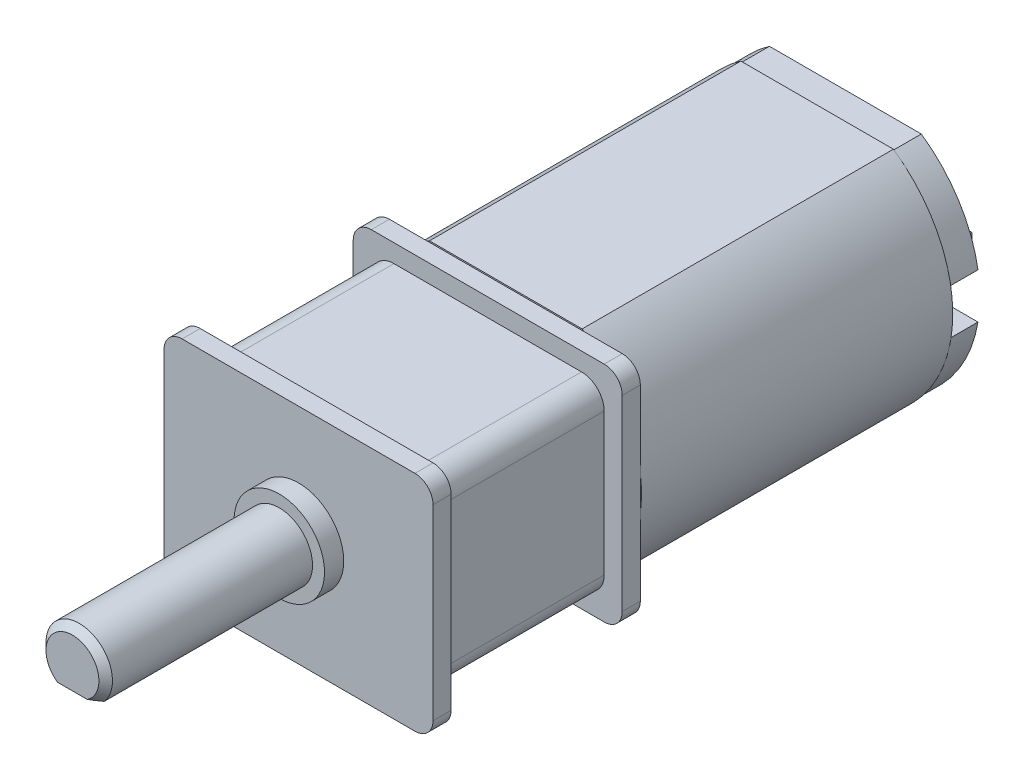
SolidWorks part; units mm, degrees
ref_plane "Front Plane" through (0, 0, 0) normal (0, 0, 1) x (1, 0, 0)
ref_plane "Top Plane" through (0, 0, 0) normal (0, 1, 0) x (1, 0, 0)
ref_plane "Right Plane" through (0, 0, 0) normal (1, 0, 0) x (0, 0, -1)
sketch "Sketch1" plane through (0, 0, 0) normal (0, 0, 1) x (1, 0, 0)
  line L1 (53.6767, -74.8935) -> (60.4267, -74.8935)
  line L3 (60.4267, -84.8935) -> (53.6767, -84.8935)
  arc A0 (53.6767, -74.8935) -> (53.6767, -84.8935) centre (57.1262, -79.8935) ccw
  arc A1 (60.4267, -74.8935) -> (60.4267, -84.8935) centre (56.9773, -79.8935) cw
extrude "Boss-Extrude1" add sketch "Sketch1" against normal blind 16.82
sketch "Sketch2" plane through (0, 0, 0) normal (0, 0, 1) x (1, 0, 0)
  line L3 (63.0017, -84.0335) -> (63.0017, -75.7535)
  line L4 (51.1017, -84.0335) -> (51.1017, -75.7535)
  line L6 (51.9017, -84.8335) -> (62.2017, -84.8335)
  line L7 (51.9017, -74.9535) -> (62.2017, -74.9535)
  arc A0 (51.9017, -74.9535) -> (51.1017, -75.7535) centre (51.9017, -75.7535) ccw
  arc A1 (51.9017, -84.8335) -> (51.1017, -84.0335) centre (51.9017, -84.0335) cw
  arc A2 (62.2017, -84.8335) -> (63.0017, -84.0335) centre (62.2017, -84.0335) ccw
  arc A3 (62.2017, -74.9535) -> (63.0017, -75.7535) centre (62.2017, -75.7535) cw
  dimension "D1" = 0.8
extrude "Boss-Extrude2" add sketch "Sketch2" along normal blind 9.17
sketch "Sketch3" plane through (0, 0, 9.17) normal (0, 0, 1) x (1, 0, 0)
  line L0 (57.0517, -74.9535) -> (57.0517, -84.8335) construction
  line L1 (62.2017, -74.9535) -> (51.9017, -74.9535) construction
  line L2 (51.9017, -84.8335) -> (62.2017, -84.8335) construction
  circle A0 centre (57.0517, -79.8935) radius 2
extrude "Boss-Extrude3" add sketch "Sketch3" along normal blind 0.85
sketch "Sketch4" plane through (0, 0, 10.02) normal (0, 0, 1) x (1, 0, 0)
  circle A0 centre (57.0517, -79.8935) radius 1.47
extrude "Boss-Extrude4" add sketch "Sketch4" along normal offset from surface (9.15 mm away) 10 up to face at (59.0517, -79.8935, 9.17) offset beyond the face yes
sketch "Sketch5" plane through (0, 0, 19.17) normal (0, 0, 1) x (1, 0, 0)
  line L0 (57.0517, -78.4235) -> (57.0517, -80.8635) construction
  line L1 (57.0517, -80.8635) -> (58.4794, -80.8635)
  line L2 (58.4794, -80.8635) -> (58.4794, -81.6355)
  line L3 (58.4794, -81.6355) -> (55.372, -81.6355)
  line L4 (55.372, -81.6355) -> (55.372, -80.8635)
  line L5 (55.372, -80.8635) -> (57.0517, -80.8635)
  circle A0 centre (57.0517, -79.8935) radius 1.47 construction
extrude "Cut-Extrude1" cut sketch "Sketch5" against normal up to surface (9.15 mm away) up to face at (58.5217, -79.8935, 10.02)
sketch "Sketch6" plane through (0, 0, -16.82) normal (0, 0, -1) x (-1, 0, 0)
  line L0 (-60.4267, -84.8935) -> (-53.6767, -74.8935) construction
  circle A0 centre (-57.0517, -79.8935) radius 4.5618
sketch "Sketch7" plane through (0, 0, -16.82) normal (0, 0, -1) x (-1, 0, 0)
  line L1 (-60.5517, -79.1435) -> (-60.8517, -79.1435)
  line L2 (-53.2517, -79.1435) -> (-53.2517, -79.8935)
  line L4 (-53.5517, -79.1435) -> (-53.5517, -80.6435)
  line L5 (-53.5517, -80.6435) -> (-53.2517, -80.6435)
  line L6 (-53.2517, -80.6435) -> (-53.2517, -79.8935)
  line L7 (-53.5517, -79.1435) -> (-53.2517, -79.1435)
  line L8 (-60.8517, -80.6435) -> (-60.8517, -79.8935)
  line L9 (-60.5517, -80.6435) -> (-60.8517, -80.6435)
  line L10 (-60.5517, -79.1435) -> (-60.5517, -80.6435)
  line L11 (-60.8517, -79.1435) -> (-60.8517, -79.8935)
  circle A0 centre (-57.0517, -79.8935) radius 2.5
  circle A1 centre (-57.0517, -79.8935) radius 7.0767
extrude "Cut-Extrude2" cut sketch "Sketch7" against normal blind 1.8
sketch "Sketch8" plane through (0, 0, -16.82) normal (0, 0, -1) x (-1, 0, 0)
  circle A1 centre (-57.0517, -79.8935) radius 2.5
  circle A2 centre (-57.0517, -79.8935) radius 2.5
  dimension "D1" = 0
extrude "Cut-Extrude3" cut sketch "Sketch8" against normal blind 0.55
ref_plane "Plane1" through (0, 0, 8.37) normal (0, 0, 1) x (1, 0, 0)
sketch "Sketch9" plane through (0, 0, 8.37) normal (0, 0, 1) x (1, 0, 0)
  line L4 (64.2017, -73.7535) -> (49.9017, -73.7535)
  line L5 (49.9017, -73.7535) -> (49.9017, -86.0335)
  line L6 (49.9017, -86.0335) -> (64.2017, -86.0335)
  line L7 (64.2017, -86.0335) -> (64.2017, -73.7535)
  line L8 (51.9017, -75.7535) -> (51.9017, -84.0335)
  line L9 (51.9017, -84.0335) -> (62.2017, -84.0335)
  line L10 (62.2017, -84.0335) -> (62.2017, -75.7535)
  line L11 (62.2017, -75.7535) -> (51.9017, -75.7535)
  line L12 (51.9017, -75.7535) -> (51.9017, -84.0335)
  line L13 (51.9017, -84.0335) -> (62.2017, -84.0335)
  line L14 (62.2017, -84.0335) -> (62.2017, -75.7535)
  line L15 (62.2017, -75.7535) -> (51.9017, -75.7535)
  dimension "D1" = 0.8
  dimension "D2" = 2
extrude "Cut-Extrude4" cut sketch "Sketch9" against normal offset from surface (7.57 mm away) 0.8 up to face at (51.7744, -76.0879, 0)
fillet "Fillet1" radius 1 4 edges at (51.9017, -84.0335, 4.585) (62.2017, -84.0335, 4.585) (51.9017, -75.7535, 4.585) (62.2017, -75.7535, 4.585)
chamfer "Chamfer2" distance 0.25 angle 45 4 edges at (53.4017, -80.6435, -16.82) (53.4017, -79.1435, -16.82) (60.7017, -80.6435, -16.82) (60.7017, -79.1435, -16.82)
sketch "Sketch10" plane through (60.8517, 0, 0) normal (1, 0, 0) x (0, 0, -1)
  circle A0 centre (15.9965, -79.8935) radius 0.35
extrude "Cut-Extrude5" cut sketch "Sketch10" against normal blind 0.8
sketch "Sketch11" plane through (53.5517, 0, 0) normal (1, 0, 0) x (0, 0, -1)
  circle A1 centre (15.9965, -79.8935) radius 0.35
  circle A2 centre (15.9965, -79.8935) radius 0.35
  dimension "D1" = 0
extrude "Cut-Extrude6" cut sketch "Sketch11" against normal blind 0.8
fillet "Fillet2" radius 0.2 1 edges at (54.5517, -79.8935, -16.27)
sketch "Sketch12" plane through (0, 0, -16.27) normal (0, 0, -1) x (-1, 0, 0)
  circle A0 centre (-57.0517, -79.8935) radius 0.825
extrude "Cut-Extrude7" cut sketch "Sketch12" against normal blind 1
sketch "Sketch13" plane through (0, 0, -15.02) normal (0, 0, -1) x (-1, 0, 0)
  line L2 (-53.3926, -73.9435) -> (-60.7109, -73.9435)
  line L3 (-60.7109, -85.8435) -> (-53.3926, -85.8435)
  line L4 (-53.6924, -74.9435) -> (-60.4111, -74.9435)
  line L5 (-60.4111, -84.8435) -> (-53.6924, -84.8435)
  line L6 (-53.6924, -74.9435) -> (-60.4111, -74.9435)
  line L7 (-60.4111, -84.8435) -> (-53.6924, -84.8435)
  arc A2 (-60.7109, -73.9435) -> (-60.7109, -85.8435) centre (-56.9773, -79.8935) ccw
  arc A3 (-53.3926, -85.8435) -> (-53.3926, -73.9435) centre (-57.1262, -79.8935) ccw
  arc A4 (-60.4111, -74.9435) -> (-60.4111, -84.8435) centre (-56.9773, -79.8935) ccw
  arc A5 (-53.6924, -84.8435) -> (-53.6924, -74.9435) centre (-57.1262, -79.8935) ccw
  arc A6 (-60.4111, -74.9435) -> (-60.4111, -84.8435) centre (-56.9773, -79.8935) ccw
  arc A7 (-53.6924, -84.8435) -> (-53.6924, -74.9435) centre (-57.1262, -79.8935) ccw
  dimension "D1" = 0.05
  dimension "D2" = 1
extrude "Cut-Extrude8" cut sketch "Sketch13" against normal blind 1.25
sketch "Sketch14" plane through (0, 0, -15.02) normal (0, 0, -1) x (-1, 0, 0)
  line L1 (-61.3762, -80.8935) -> (-63.3161, -80.8935)
  line L3 (-61.3762, -80.8935) -> (-61.3762, -78.8935)
  line L4 (-61.3762, -78.8935) -> (-63.3161, -78.8935)
  line L5 (-63.3161, -78.8935) -> (-63.3161, -80.8935)
  line L7 (-50.7874, -78.8935) -> (-50.7874, -80.8935)
  line L8 (-52.7273, -78.8935) -> (-50.7874, -78.8935)
  line L9 (-52.7273, -80.8935) -> (-52.7273, -78.8935)
  line L10 (-52.7273, -80.8935) -> (-50.7874, -80.8935)
extrude "Cut-Extrude9" cut sketch "Sketch14" against normal blind 1.25
chamfer "Chamfer3" distance 0.3 angle 45 1 edges at (57.0517, -78.4235, 19.17)
